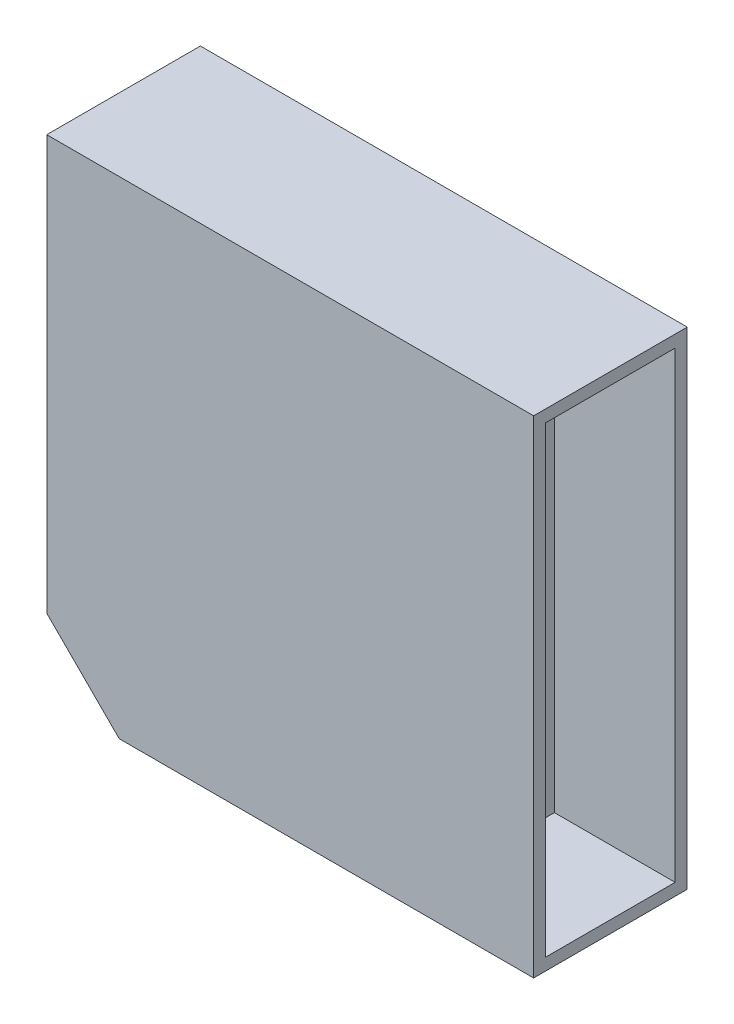
SolidWorks part; units mm, degrees
ref_plane "前视基准面" through (0, 0, 0) normal (0, 0, 1) x (1, 0, 0)
ref_plane "上视基准面" through (0, 0, 0) normal (0, 1, 0) x (1, 0, 0)
ref_plane "右视基准面" through (0, 0, 0) normal (1, 0, 0) x (0, 0, -1)
sketch "草图1" plane through (0, 0, 0) normal (0, 0, 1) x (1, 0, 0)
  line L1 (-10.08, 10.08) -> (10.08, 10.08)
  line L2 (-10.08, 10.08) -> (-10.08, -10.08)
  line L3 (-10.08, -10.08) -> (10.08, -10.08)
  line L4 (10.08, 10.08) -> (10.08, -10.08)
  line L5 (-10.08, 10.08) -> (10.08, -10.08) construction
  line L6 (-10.08, -10.08) -> (10.08, 10.08) construction
  point P0 (0, 0)
  dimension "D1" = 20.16
  dimension "D2" = 20.16
extrude "凸台-拉伸1" add sketch "草图1" along normal blind 6.36
sketch "草图2" plane through (10.08, 0, 0) normal (1, 0, 0) x (0, 0, -1)
  line L8 (-0.5, -9.58) -> (-0.5, 9.58)
  line L9 (-0.5, 9.58) -> (-5.86, 9.58)
  line L10 (-5.86, 9.58) -> (-5.86, -9.58)
  line L11 (-5.86, -9.58) -> (-0.5, -9.58)
  line L12 (-0.5, -9.58) -> (-0.5, 9.58)
  line L13 (-0.5, 9.58) -> (-5.86, 9.58)
  line L14 (-5.86, 9.58) -> (-5.86, -9.58)
  line L15 (-5.86, -9.58) -> (-0.5, -9.58)
  dimension "D1" = 0.5
extrude "切除-拉伸1" cut sketch "草图2" against normal blind 5
chamfer "倒角1" distance 3 angle 45 1 edges at (-10.08, -10.08, 3.18)
